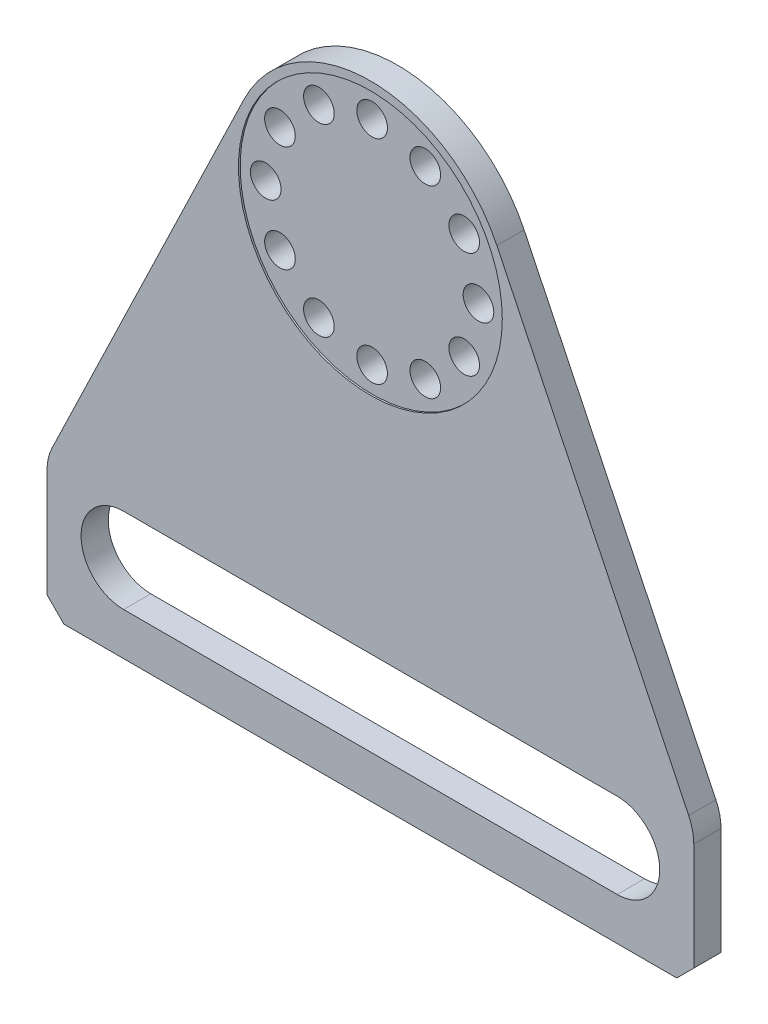
SolidWorks part; units mm, degrees
ref_plane "前视基准面" through (0, 0, 0) normal (0, 0, 1) x (1, 0, 0)
ref_plane "上视基准面" through (0, 0, 0) normal (0, 1, 0) x (1, 0, 0)
ref_plane "右视基准面" through (0, 0, 0) normal (1, 0, 0) x (0, 0, -1)
sketch "草图1" plane through (0, 0, 0) normal (0, 0, 1) x (1, 0, 0)
  line L0 (-74.3068, 35.8434) -> (-187.0207, -197.8235)
  line L1 (-190, -210.8575) -> (-190, -284)
  line L2 (-190, -284) -> (0, -284)
  line L3 (0, 0) -> (0, -285.4372) construction
  line L4 (190, -284) -> (0, -284)
  line L5 (190, -210.8575) -> (190, -284)
  line L6 (74.3068, 35.8434) -> (187.0207, -197.8235)
  arc A0 (74.3068, 35.8434) -> (-74.3068, 35.8434) centre (0, 0) ccw
  arc A1 (190, -210.8575) -> (187.0207, -197.8235) centre (160, -210.8575) ccw
  arc A2 (-187.0207, -197.8235) -> (-190, -210.8575) centre (-160, -210.8575) ccw
  point P12 (0, 0)
  point P14 (190, -204)
  point P17 (-190, -204)
  dimension "D1" = 165
  dimension "D3" = 284
  dimension "D5" = 30
  dimension "D2" = 80
  dimension "D4" = 190
extrude "凸台-拉伸1" add sketch "草图1" along normal blind 16
sketch "草图2" plane through (0, 0, 16) normal (0, 0, 1) x (1, 0, 0)
  circle A0 centre (0, 0) radius 77.5
  dimension "D1" = 155
extrude "切除-拉伸1" cut sketch "草图2" against normal blind 1
sketch "草图3" plane through (0, 0, 15) normal (0, 0, 1) x (1, 0, 0)
  line L0 (0, 0) -> (0, 62.5) construction
  circle A0 centre (0, 0) radius 62.5 construction
  circle A1 centre (0, 62.5) radius 9
  circle A2 centre (31.25, 54.1266) radius 9
  circle A3 centre (54.1266, 31.25) radius 9
  circle A4 centre (62.5, 0) radius 9
  circle A5 centre (54.1266, -31.25) radius 9
  circle A6 centre (31.25, -54.1266) radius 9
  circle A7 centre (0, -62.5) radius 9
  circle A8 centre (-31.25, -54.1266) radius 9
  circle A9 centre (-54.1266, -31.25) radius 9
  circle A10 centre (-62.5, 0) radius 9
  circle A11 centre (-54.1266, 31.25) radius 9
  circle A12 centre (-31.25, 54.1266) radius 9
  point P5 (68.4208, 6.5438)
  point P6 (0, 0)
  dimension "D1" = 125
  dimension "D2" = 18
  dimension "D4" = 62.5
  dimension "D3" = 12
extrude "切除-拉伸2" cut sketch "草图3" against normal up to next
sketch "草图4" plane through (0, 0, 16) normal (0, 0, 1) x (1, 0, 0)
  line L0 (-145, -234) -> (145, -234) construction
  line L1 (-145, -209) -> (145, -209)
  line L2 (-145, -259) -> (145, -259)
  line L3 (-190, -284) -> (190, -284) construction
  arc A0 (-145, -209) -> (-145, -259) centre (-145, -234) ccw
  arc A1 (145, -259) -> (145, -209) centre (145, -234) ccw
  point P2 (0, -234)
  dimension "D1" = 25
  dimension "D4" = 50
  dimension "D2" = 290
  dimension "D3" = 145
extrude "切除-拉伸3" cut sketch "草图4" against normal up to next
chamfer "倒角1" distance 10 angle 45 2 edges at (-190, -284, 8) (190, -284, 8)
